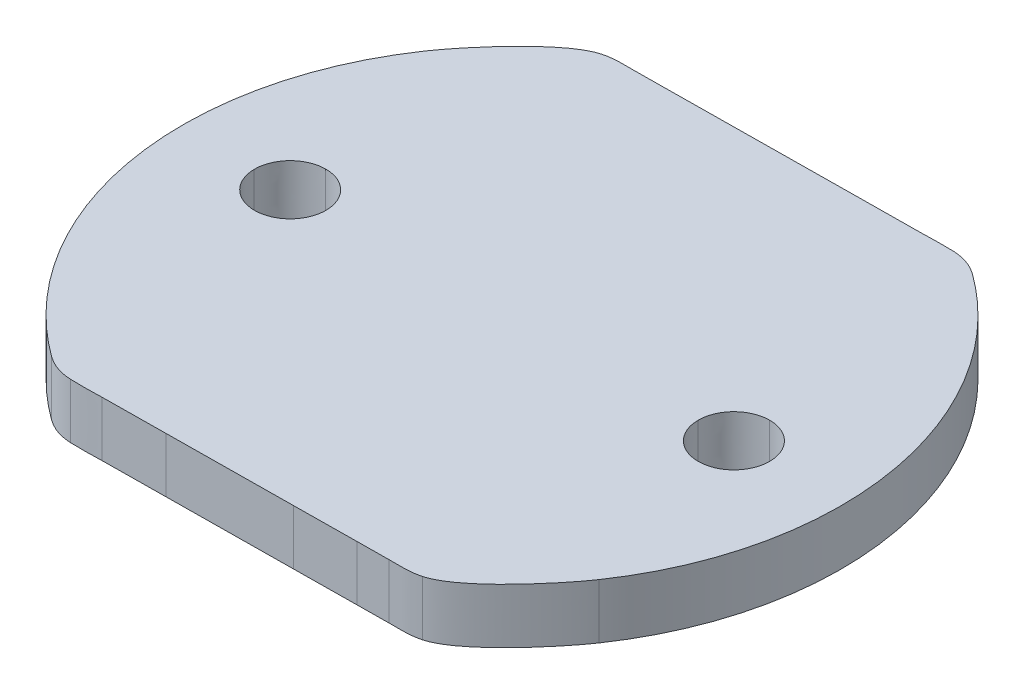
SolidWorks part; units mm, degrees
ref_plane "Front Plane" through (0, 0, 0) normal (0, 0, 1) x (1, 0, 0)
ref_plane "Top Plane" through (0, 0, 0) normal (0, 1, 0) x (1, 0, 0)
ref_plane "Right Plane" through (0, 0, 0) normal (1, 0, 0) x (0, 0, -1)
sketch "Sketch1" plane through (0, 0, 0) normal (0, 1, 0) x (1, 0, 0)
  line L0 (60.8717, 62.8884) -> (60.8717, 62.8915)
  spline S0 degree 3 poles (59.597, 32.3955) (59.6175, 30.1217) (61.4849, 28.2889) (63.7656, 28.3165) knots 0 0 0 0 1 1 1 1
  spline S1 degree 3 poles (63.7656, 28.3165) (66.0462, 28.3365) (67.8721, 30.2044) (67.8515, 32.4851) knots 0 0 0 0 1 1 1 1
  spline S2 degree 3 poles (67.8515, 32.4851) (67.831, 34.7588) (65.9635, 36.5916) (63.6829, 36.5709) knots 0 0 0 0 1 1 1 1
  spline S3 degree 3 poles (63.6829, 36.5709) (61.4022, 36.5409) (59.5695, 34.6761) (59.597, 32.3955) knots 0 0 0 0 1 1 1 1
  spline S4 degree 3 poles (17.057, 31.9683) (17.0776, 29.6876) (15.2449, 27.8204) (12.9711, 27.7997) knots 0 0 0 0 1 1 1 1
  spline S5 degree 3 poles (12.9711, 27.7997) (10.6904, 27.7747) (8.8232, 29.605) (8.8025, 31.8856) knots 0 0 0 0 1 1 1 1
  spline S6 degree 3 poles (8.8025, 31.8856) (8.775, 34.1594) (10.6078, 36.0266) (12.8884, 36.0542) knots 0 0 0 0 1 1 1 1
  spline S7 degree 3 poles (12.8884, 36.0542) (15.1622, 36.0742) (17.0294, 34.2489) (17.057, 31.9683) knots 0 0 0 0 1 1 1 1
  spline S8 degree 3 poles (60.8717, 62.8915) (59.8244, 63.6632) (58.7702, 64.0421) (57.468, 64.1179) knots 0 0 0 0 1 1 1 1
  spline S9 degree 3 poles (57.468, 64.1179) (56.2484, 64.1799) (55.0357, 64.1029) (53.823, 64.0879) knots 0 0 0 0 1 1 1 1
  spline S10 degree 3 poles (53.823, 64.0879) (51.3908, 64.0629) (48.9586, 64.0379) (46.5263, 64.0189) knots 0 0 0 0 1 1 1 1
  spline S11 degree 3 poles (46.5263, 64.0189) (41.6618, 63.9639) (36.7974, 63.9154) (31.9329, 63.8674) knots 0 0 0 0 1 1 1 1
  spline S12 degree 3 poles (31.9329, 63.8674) (29.4938, 63.8374) (27.0615, 63.8174) (24.6293, 63.7914) knots 0 0 0 0 1 1 1 1
  spline S13 degree 3 poles (24.6293, 63.7914) (23.4097, 63.7764) (22.1971, 63.7714) (20.9775, 63.7564) knots 0 0 0 0 1 1 1 1
  spline S14 degree 3 poles (20.9775, 63.7564) (19.7579, 63.7414) (18.559, 63.8389) (17.3464, 63.5084) knots 0 0 0 0 1 1 1 1
  spline S15 degree 3 poles (17.3464, 63.5084) (13.8599, 62.5576) (8.5751, 56.1841) (6.825, 53.6141) knots 0 0 0 0 1 1 1 1
  spline S16 degree 3 poles (6.825, 53.6141) (-4.716, 36.6573) (-0.7611, 13.6097) (15.7754, 1.4691) knots 0 0 0 0 1 1 1 1
  spline S17 degree 3 poles (15.7754, 1.4691) (16.8296, 0.6974) (17.8769, 0.3185) (19.186, 0.2496) knots 0 0 0 0 1 1 1 1
  spline S18 degree 3 poles (19.186, 0.2496) (20.3987, 0.1806) (21.6114, 0.2546) (22.8309, 0.2696) knots 0 0 0 0 1 1 1 1
  spline S19 degree 3 poles (22.8309, 0.2696) (25.2563, 0.2946) (27.6954, 0.3196) (30.1277, 0.3456) knots 0 0 0 0 1 1 1 1
  spline S20 degree 3 poles (30.1277, 0.3456) (34.9921, 0.3956) (39.8566, 0.4421) (44.7211, 0.4901) knots 0 0 0 0 1 1 1 1
  spline S21 degree 3 poles (44.7211, 0.4901) (47.1533, 0.5201) (49.5856, 0.5401) (52.0247, 0.5661) knots 0 0 0 0 1 1 1 1
  spline S22 degree 3 poles (52.0247, 0.5661) (53.2374, 0.5811) (54.4569, 0.5961) (55.6696, 0.6011) knots 0 0 0 0 1 1 1 1
  spline S23 degree 3 poles (55.6696, 0.6011) (56.8892, 0.6161) (58.088, 0.5186) (59.3076, 0.8491) knots 0 0 0 0 1 1 1 1
  spline S24 degree 3 poles (59.3076, 0.8491) (62.7941, 1.7999) (68.0788, 8.1803) (69.822, 10.7434) knots 0 0 0 0 1 1 1 1
  spline S25 degree 3 poles (69.822, 10.7434) (81.3631, 27.7002) (77.4082, 50.7479) (60.8717, 62.8884) knots 0 0 0 0 1 1 1 1
extrude "Boss-Extrude1" add sketch "Sketch1" along normal blind 6.35 contours S16 S17 S18 S19 S20 S21 S22 S23 S24 S25 L0 S8 S9 S10 S11 S12 S13 S14 S15
sketch "Sketch2" plane through (0, 6.35, 0) normal (0, 1, 0) x (1, 0, 0)
  line L0 (12.9338, 31.931) -> (63.7307, 32.4501) construction
  circle A0 centre (12.9338, 31.931) radius 4.1234 construction
  circle A1 centre (63.7307, 32.4501) radius 4.1209 construction
  spline S0 degree 3 poles (12.8884, 36.0542) (10.6078, 36.0266) (8.775, 34.1594) (8.8025, 31.8856) knots 0 0 0 0 1 1 1 1 construction
  spline S1 degree 3 poles (12.9711, 27.7997) (15.2449, 27.8204) (17.0776, 29.6876) (17.057, 31.9683) knots 0 0 0 0 1 1 1 1 construction
  spline S4 degree 3 poles (67.8515, 32.4851) (67.831, 34.7588) (65.9635, 36.5916) (63.6829, 36.5709) knots 0 0 0 0 1 1 1 1 construction
  spline S5 degree 3 poles (63.6829, 36.5709) (61.4022, 36.5409) (59.5695, 34.6761) (59.597, 32.3955) knots 0 0 0 0 1 1 1 1 construction
  point P12 (38.3322, 32.1905)
